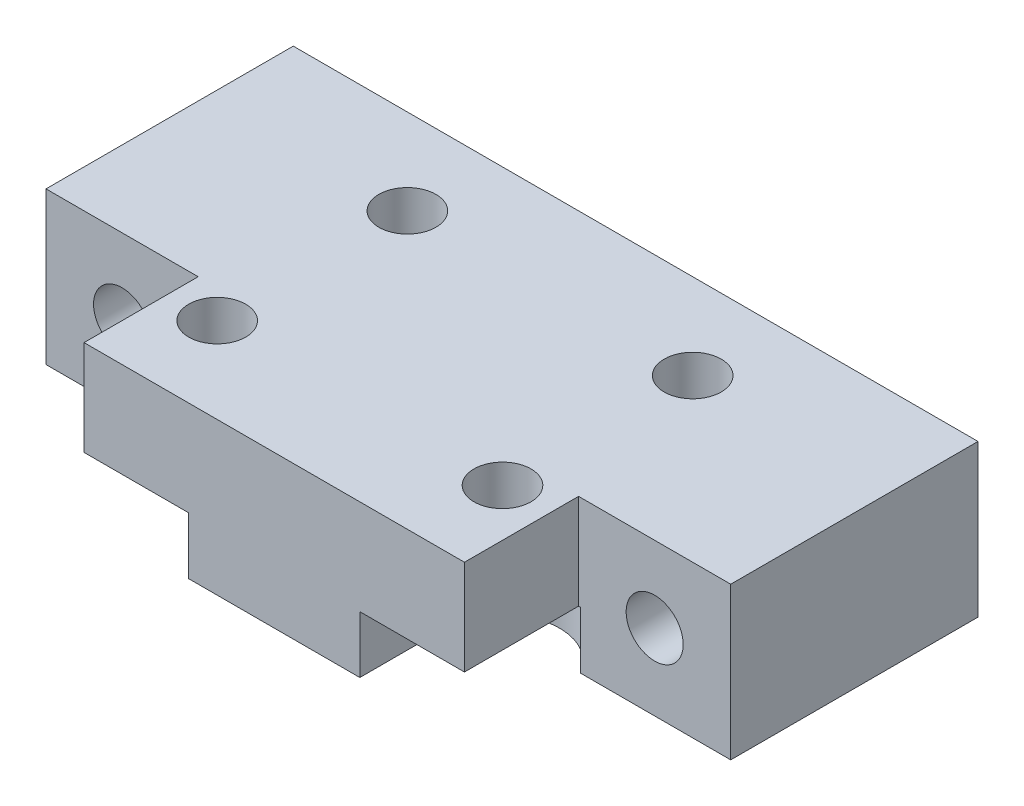
SolidWorks part; units mm, degrees
ref_plane "前视基准面" through (0, 0, 0) normal (0, 0, 1) x (1, 0, 0)
ref_plane "上视基准面" through (0, 0, 0) normal (0, 1, 0) x (1, 0, 0)
ref_plane "右视基准面" through (0, 0, 0) normal (1, 0, 0) x (0, 0, -1)
other "Configuration Table"
sketch "草图1" plane through (0, 0, 0) normal (0, 1, 0) x (1, 0, 0)
  line L0 (0, 0) -> (0, 19) construction
  line L1 (-18, 19) -> (18, 19)
  line L4 (-18, 19) -> (-18, 6)
  line L5 (-18, 6) -> (-10, 6)
  line L6 (-10, 6) -> (-10, 0)
  line L7 (-10, 0) -> (10, 0)
  line L8 (18, 6) -> (10, 6)
  line L9 (18, 19) -> (18, 6)
  line L10 (10, 6) -> (10, 0)
  line L11 (0, 9.5) -> (18, 9.5) construction
  circle A2 centre (7.5, 14.5) radius 1.5
  circle A3 centre (7.5, 4.5) radius 1.5
  circle A4 centre (-7.5, 4.5) radius 1.5
  circle A5 centre (-7.5, 14.5) radius 1.5
  point P5 (0, 19)
  point P8 (0, 0)
  dimension "D5" = 15
  dimension "D6" = 10
  dimension "D7" = 3
  dimension "D1" = 13
  dimension "D2" = 20
  dimension "D3" = 19
  dimension "D4" = 36
extrude "凸台-拉伸1" add sketch "草图1" along normal blind 8
sketch "草图2" plane through (0, 0, -19) normal (0, 0, -1) x (-1, 0, 0)
  line L0 (0, 8) -> (0, 0) construction
  line L1 (-18, 8) -> (18, 8) construction
  line L2 (0, 4) -> (-14, 4) construction
  circle A0 centre (-14, 4) radius 1.5
  circle A1 centre (14, 4) radius 1.5
  dimension "D1" = 3
  dimension "D2" = 28
extrude "切除-拉伸1" cut sketch "草图2" against normal through all
sketch "草图3" plane through (0, 0, 0) normal (0, -1, 0) x (1, 0, 0)
  circle A2 centre (-7.5, -14.5) radius 3
  circle A3 centre (7.5, -14.5) radius 3
  dimension "D1" = 6
extrude "切除-拉伸2" cut sketch "草图3" against normal blind 3
sketch "草图4" plane through (0, 0, 0) normal (0, -1, 0) x (1, 0, 0)
  line L0 (0, 0) -> (0, -19) construction
  line L1 (-4.5, -4.5) -> (-10, -4.5)
  line L2 (-4.5, -4.5) -> (-4.5, 0)
  line L3 (-4.5, 0) -> (-10, 0)
  line L4 (-10, -4.5) -> (-10, 0)
  line L5 (18, -19) -> (-18, -19) construction
  line L6 (10, -4.5) -> (10, 0)
  line L7 (4.5, 0) -> (10, 0)
  line L8 (4.5, -4.5) -> (4.5, 0)
  line L9 (4.5, -4.5) -> (10, -4.5)
  circle A0 centre (-7.5, -4.5) radius 3
  circle A1 centre (7.5, -4.5) radius 3
  line M11 (18, -6) -> (10, -6)
  line M12 (10, -6) -> (10, 0)
  line M13 (10, 0) -> (-10, 0)
  line M14 (-10, 0) -> (-10, -6)
  line M15 (-10, -6) -> (-18, -6)
  circle M16 centre (7.5, -4.5) radius 1.5
  circle M17 centre (-7.5, -4.5) radius 1.5
  dimension "D1" = 6
extrude "切除-拉伸3" cut sketch "草图4" against normal blind 3 contours A0 L2 M13 M14 | L1 A0 L4 M17 | A0 L1 M15 M17 M14 | A1 L9 M16 M12 | A1 L9 M11 M12 M16 | L8 A1 L6 M13
